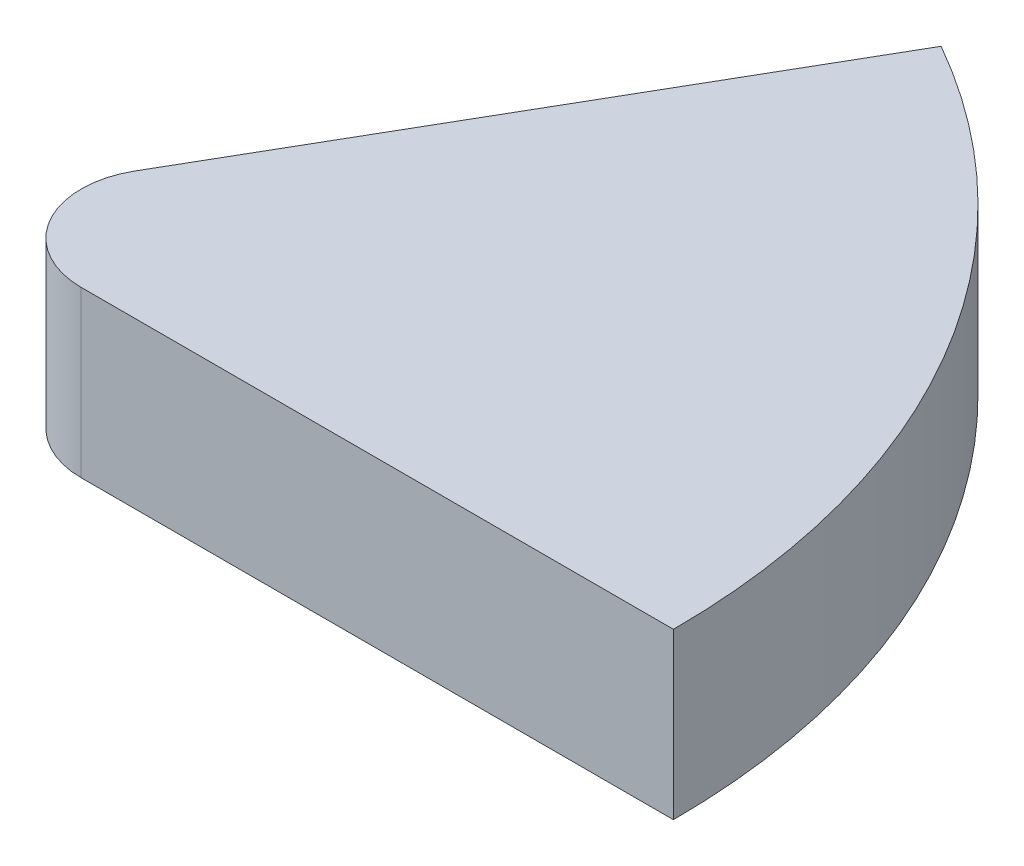
SolidWorks part; units mm, degrees
material "Pine"
ref_plane "Front Plane" through (0, 0, 0) normal (0, 0, 1) x (1, 0, 0)
ref_plane "Top Plane" through (0, 0, 0) normal (0, 1, 0) x (1, 0, 0)
ref_plane "Right Plane" through (0, 0, 0) normal (1, 0, 0) x (0, 0, -1)
sketch "Sketch1" plane through (0, 0, 0) normal (0, 1, 0) x (1, 0, 0)
  line L59 (-38.1, 73.7857) -> (-38.1, 0) construction
  line L60 (-38.1, 0) -> (38.1, 0) construction
  line L62 (38.1, 0) -> (38.1, 73.7857) construction
  line L63 (38.1, 73.7857) -> (-38.1, 73.7857) construction
  line L64 (-4.7625, 73.7857) -> (-38.8388, 14.7637)
  line L70 (-4.7625, 73.7857) -> (9.525, 98.5324) construction
  line L71 (16.8573, 111.2324) -> (9.525, 98.5324) construction
  line L72 (38.1, 0) -> (66.675, 0) construction
  line L73 (66.675, 473.5715) -> (66.675, -326.5285) construction
  line L75 (-30.315, 0) -> (38.1, 0)
  line L76 (19.05, 0) -> (-25.4, 0) construction
  arc A4 (38.1, 0) -> (-4.7625, 73.7857) centre (-46.8405, 0) ccw
  arc A15 (-30.315, 0) -> (-38.8388, 14.7637) centre (-30.315, 9.8425) cw
  arc A17 (-25.4, 0) -> (-34.3883, -13.8532) centre (-25.4, -9.8425) ccw construction
  point P4 (0, 0)
  point P5 (-19.8586, 8.6761)
  point P16 (-26.7434, 11.1233)
  dimension "D1" = 76.2
extrude "Boss-Extrude1" add sketch "Sketch1" along normal blind 19.05
